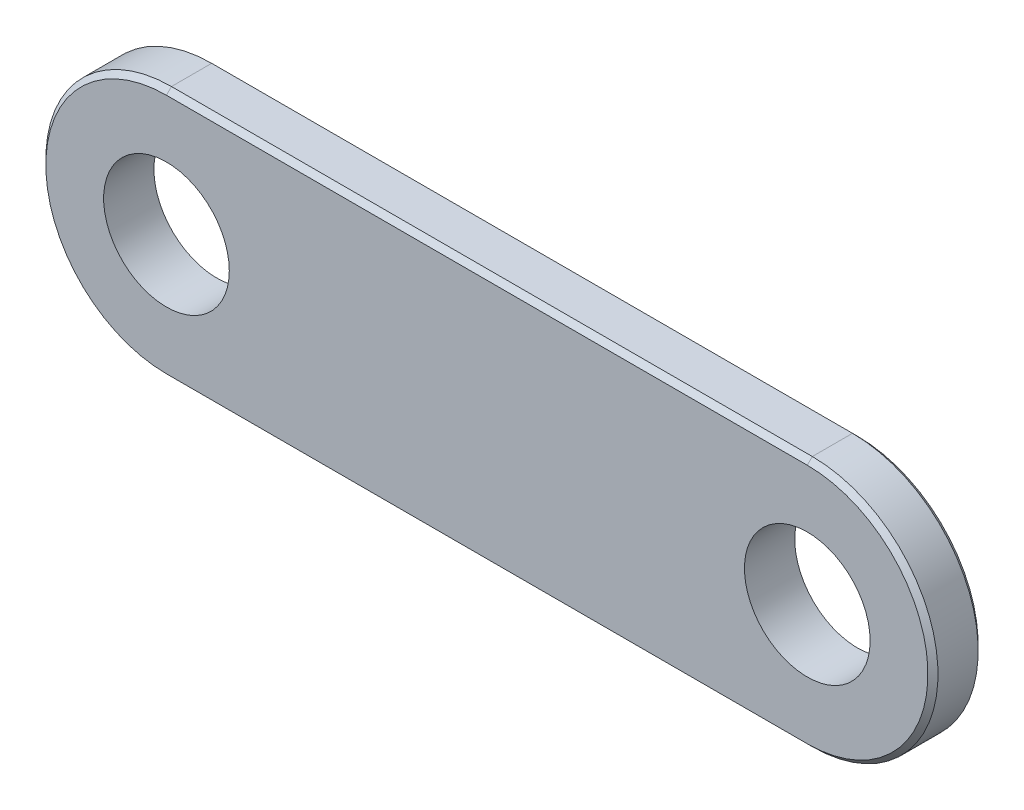
SolidWorks part; units mm, degrees
ref_plane "前基準面" through (0, 0, 0) normal (0, 0, 1) x (1, 0, 0)
ref_plane "上基準面" through (0, 0, 0) normal (0, 1, 0) x (1, 0, 0)
ref_plane "右基準面" through (0, 0, 0) normal (1, 0, 0) x (0, 0, -1)
sketch "草圖1" plane through (0, 0, 0) normal (0, 0, 1) x (1, 0, 0)
  line L0 (-127.5, 0) -> (127.5, 0) construction
  line L1 (-127.5, 50) -> (127.5, 50)
  line L2 (-127.5, -50) -> (127.5, -50)
  arc A0 (-127.5, 50) -> (-127.5, -50) centre (-127.5, 0) ccw
  arc A1 (127.5, -50) -> (127.5, 50) centre (127.5, 0) ccw
  circle A2 centre (-127.5, 0) radius 25
  circle A3 centre (127.5, 0) radius 25
  point P2 (0, 0)
  dimension "D3" = 50
  dimension "D4" = 50
  dimension "D1" = 100
  dimension "D2" = 255
extrude "填料-伸長1" add sketch "草圖1" along normal blind 20
chamfer "導角1" distance 2 angle 45 8 edges at (177.5, 0, 20) (0, 50, 20) (0, -50, 20) (-177.5, 0, 20) (177.5, 0, 0) (0, 50, 0) (0, -50, 0) (-177.5, 0, 0)
